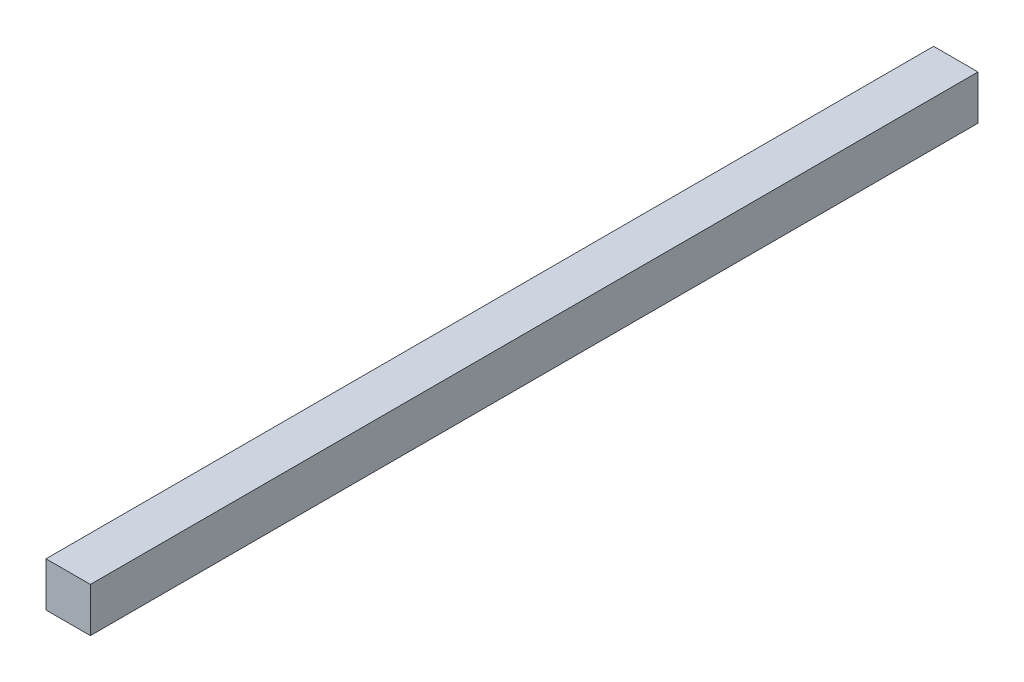
SolidWorks part; units mm, degrees
material "Plain Carbon Steel"
ref_plane "Front Plane" through (0, 0, 0) normal (0, 0, 1) x (1, 0, 0)
ref_plane "Top Plane" through (0, 0, 0) normal (0, 1, 0) x (1, 0, 0)
ref_plane "Right Plane" through (0, 0, 0) normal (1, 0, 0) x (0, 0, -1)
sketch "Sketch1" plane through (0, 0, 0) normal (0, 0, 1) x (1, 0, 0)
  line L1 (-115, 230) -> (115, 230)
  line L2 (-115, 230) -> (-115, 0)
  line L3 (-115, 0) -> (115, 0)
  line L4 (115, 230) -> (115, 0)
  dimension "D1" = 230
extrude "Boss-Extrude1" add sketch "Sketch1" along normal blind 4600
shell "Shell1" thickness 20
sketch "Sketch2" plane through (115, 0, 0) normal (1, 0, 0) x (0, 0, -1)
  line L0 (-4600, 230) -> (0, 230) construction
  line L1 (-4050, 230) -> (-4050, 0) construction
  line L2 (-4600, 0) -> (0, 0) construction
  line L3 (-4600, 0) -> (-4600, 230) construction
  circle A0 centre (-4050, 115) radius 25
  dimension "D2" = 50
  dimension "D1" = 550
extrude "Boss-Extrude2" add sketch "Sketch2" against normal through all
